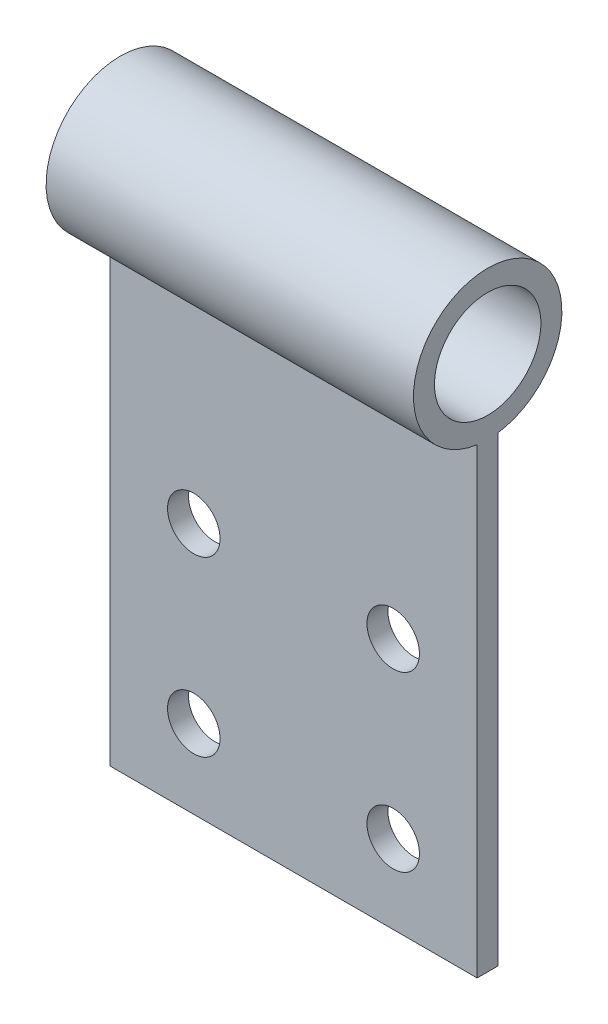
SolidWorks part; units mm, degrees
ref_plane "Front Plane" through (0, 0, 0) normal (0, 0, 1) x (1, 0, 0)
ref_plane "Top Plane" through (0, 0, 0) normal (0, 1, 0) x (1, 0, 0)
ref_plane "Right Plane" through (0, 0, 0) normal (1, 0, 0) x (0, 0, -1)
sketch "Sketch1" plane through (0, 0, 0) normal (0, 0, 1) x (1, 0, 0)
  line L1 (0, 0) -> (35, 0)
  line L2 (0, 0) -> (0, 40)
  line L3 (0, 40) -> (35, 40)
  line L4 (35, 0) -> (35, 40)
  dimension "D1" = 35
  dimension "D2" = 40
extrude "Boss-Extrude1" add sketch "Sketch1" along normal blind 2
sketch "Sketch2" plane through (0, 0, 0) normal (0, 0, -1) x (-1, 0, 0)
  line L0 (-35, 24) -> (0, 24) construction
  line L1 (-35, 7.5) -> (0, 7.5) construction
  line L2 (-27, 24) -> (-27, 0) construction
  line L3 (-8, 24) -> (-8, 0) construction
  line L4 (0, 0) -> (0, 40)
  line L5 (0, 40) -> (-35, 40)
  line L6 (-35, 40) -> (-35, 0)
  line L7 (-35, 0) -> (0, 0)
  line L8 (0, 0) -> (0, 40) construction
  line L9 (0, 40) -> (-35, 40) construction
  line L10 (-35, 40) -> (-35, 0) construction
  line L11 (-35, 0) -> (0, 0) construction
  circle A0 centre (-27, 24) radius 2.5
  circle A1 centre (-8, 24) radius 2.5
  circle A2 centre (-8, 7.5) radius 2.5
  circle A3 centre (-27, 7.5) radius 2.5
  dimension "D6" = 5
  dimension "D7" = 5
  dimension "D8" = 5
  dimension "D9" = 5
  dimension "D2" = 7.5
  dimension "D3" = 24
  dimension "D4" = 8
  dimension "D5" = 8
  dimension "D1" = 0
extrude "Cut-Extrude1" cut sketch "Sketch2" against normal through all
sketch "Sketch3" plane through (0, 0, 0) normal (-1, 0, 0) x (0, 0, 1)
  line L0 (2, 40) -> (2, 0) construction
  line L1 (0, 40) -> (2, 40)
  line L2 (0, 40) -> (0, 44)
  line L3 (0, 44) -> (2, 44) construction
  line L4 (2, 40) -> (2, 44)
  line L5 (1, 40) -> (1, 51) construction
  arc A0 (0, 44) -> (2, 44) centre (1, 51) cw
  circle A1 centre (1, 51) radius 5.0711
  dimension "D3" = 2
  dimension "D1" = 4
  dimension "D2" = 7
extrude "Boss-Extrude2" add sketch "Sketch3" against normal up to surface (35 mm away) up to face at (35, 20, 1)
